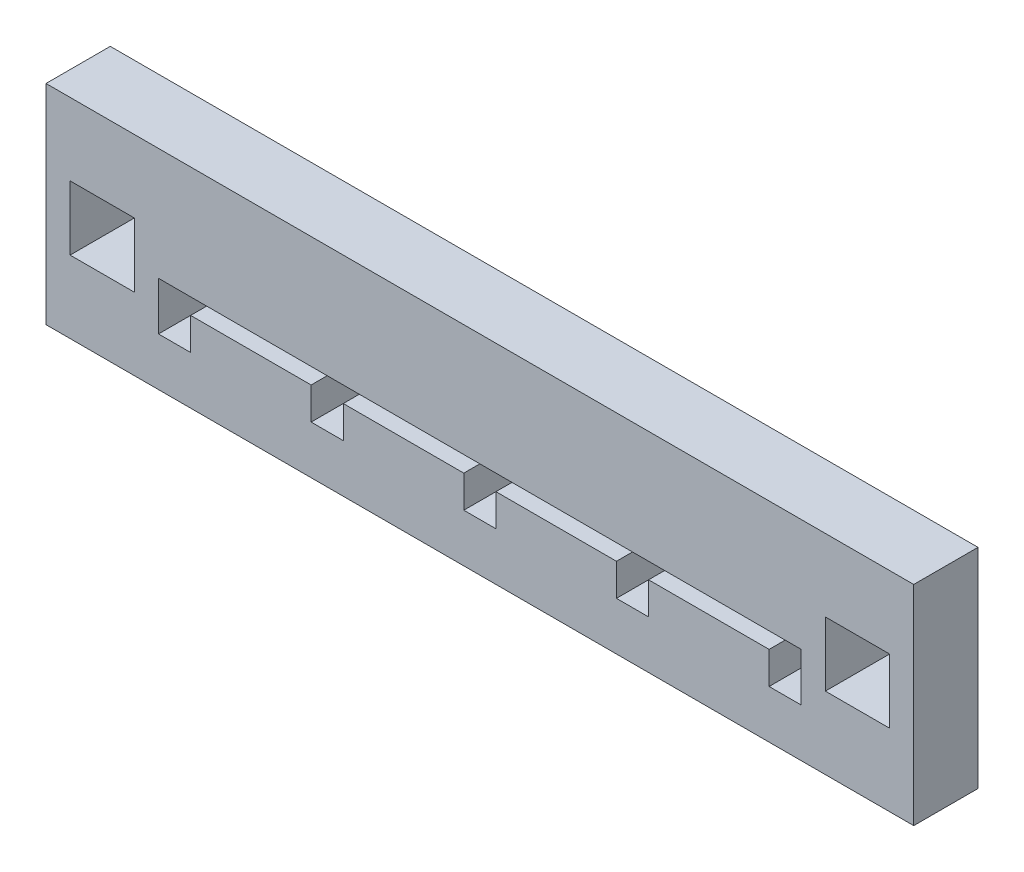
SolidWorks part; units mm, degrees
ref_plane "Front Plane" through (0, 0, 0) normal (0, 0, 1) x (1, 0, 0)
ref_plane "Top Plane" through (0, 0, 0) normal (0, 1, 0) x (1, 0, 0)
ref_plane "Right Plane" through (0, 0, 0) normal (1, 0, 0) x (0, 0, -1)
sketch "Sketch1" plane through (0, 0, 0) normal (0, 0, 1) x (1, 0, 0)
  line L0 (0, 5.3663) -> (7, 5.3663) construction
  line L1 (0, 0) -> (54, 0)
  line L2 (0, 0) -> (0, 13)
  line L3 (0, 13) -> (54, 13)
  line L4 (54, 0) -> (54, 13)
  line L5 (7, 3) -> (47, 3) construction
  line L6 (7, 3) -> (7, 6)
  line L7 (7, 6) -> (47, 6)
  line L8 (47, 3) -> (47, 6)
  line L9 (7, 3) -> (9, 3)
  line L10 (15.9975, 3) -> (15.9975, 0) construction
  line L12 (27, 6) -> (27, 13) construction
  line L13 (9, 3) -> (9, 5)
  line L14 (47, 6.444) -> (54, 6.444) construction
  line L15 (9, 5) -> (16.5, 5)
  line L16 (16.5, 3) -> (16.5, 5)
  line L18 (18.5, 3) -> (18.5, 5)
  line L19 (18.5, 5) -> (26, 5)
  line L20 (26, 3) -> (26, 5)
  line L22 (28, 3) -> (28, 5)
  line L23 (28, 5) -> (35.5, 5)
  line L24 (35.5, 3) -> (35.5, 5)
  line L26 (37.5, 3) -> (37.5, 5)
  line L27 (37.5, 5) -> (45, 5)
  line L28 (45, 3) -> (45, 5)
  line L29 (16.5, 3) -> (18.5, 3)
  line L30 (26, 3) -> (28, 3)
  line L31 (35.5, 3) -> (37.5, 3)
  line L32 (45, 3) -> (47, 3)
  line L33 (52.5, 4.5) -> (48.5, 4.5)
  line L34 (1.5, 8.5) -> (5.5, 8.5)
  line L35 (1.5, 8.5) -> (1.5, 4.5)
  line L36 (1.5, 4.5) -> (5.5, 4.5)
  line L37 (5.5, 8.5) -> (5.5, 4.5)
  line L42 (48.5, 8.5) -> (48.5, 4.5)
  line L43 (52.5, 8.5) -> (48.5, 8.5)
  line L44 (52.5, 8.5) -> (52.5, 4.5)
  line L45 (3.8799, 0) -> (3.8799, 4.5) construction
  line L47 (3.8799, 8.5) -> (3.8799, 13) construction
  dimension "D1" = 40
  dimension "D2" = 7
  dimension "D3" = 1
  dimension "D4" = 2
  dimension "D5" = 2
  dimension "D6" = 3
  dimension "D7" = 4
  dimension "D8" = 4
  dimension "D9" = 13
  dimension "D11" = 1.5
extrude "Boss-Extrude1" add sketch "Sketch1" along normal blind 4
